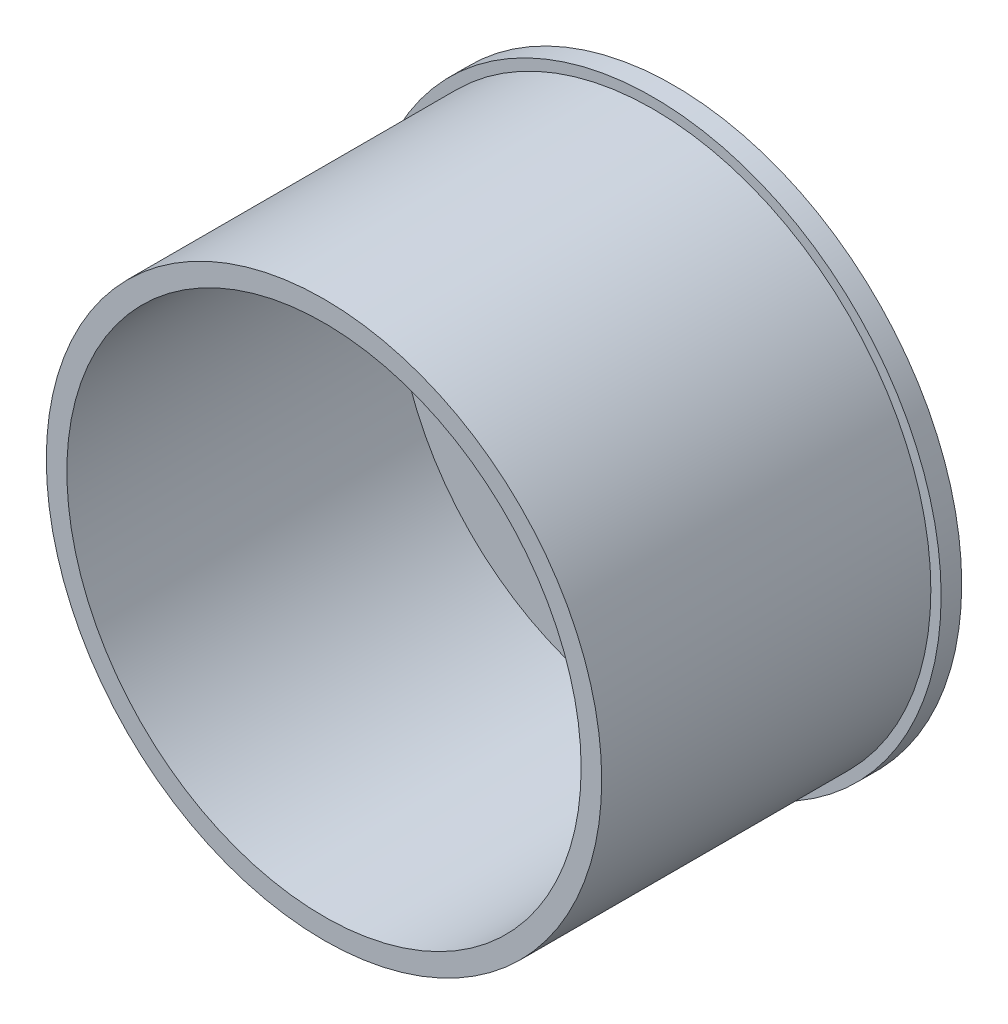
SolidWorks part; units mm, degrees
material "6061 Alloy"
ref_plane "Front Plane" through (0, 0, 0) normal (0, 0, 1) x (1, 0, 0)
ref_plane "Top Plane" through (0, 0, 0) normal (0, 1, 0) x (1, 0, 0)
ref_plane "Right Plane" through (0, 0, 0) normal (1, 0, 0) x (0, 0, -1)
sketch "Sketch1" plane through (0, 0, 0) normal (0, 0, 1) x (1, 0, 0)
  circle A0 centre (0, 0) radius 88.9
  dimension "D1" = 177.8
extrude "Boss-Extrude1" add sketch "Sketch1" along normal blind 6.35
sketch "Sketch2" plane through (0, 0, 0) normal (0, 0, -1) x (-1, 0, 0)
  line L0 (-0.0917, 3.175) -> (0.0917, -3.175) construction
  line L3 (3.082, 3.2667) -> (3.2654, -3.0833)
  line L4 (-3.2654, 3.0833) -> (-3.082, -3.2667)
  arc A2 (3.082, 3.2667) -> (-3.2654, 3.0833) centre (-0.0917, 3.175) ccw
  arc A3 (-3.082, -3.2667) -> (3.2654, -3.0833) centre (0.0917, -3.175) ccw
  circle A4 centre (19.05, 0) radius 3.302
  point P2 (0, 0)
  dimension "D2" = 6.35
  dimension "D3" = 6.604
  dimension "D1" = 6.35
  dimension "D4" = 19.05
extrude "Cut-Extrude1" cut sketch "Sketch2" against normal through all
sketch "Sketch3" plane through (0, 0, 6.35) normal (0, 0, 1) x (1, 0, 0)
  circle A0 centre (0, 0) radius 79.375
  circle A2 centre (0, 0) radius 85.725
  dimension "D1" = 6.35
  dimension "D2" = 158.75
extrude "Boss-Extrude2" add sketch "Sketch3" along normal blind 101.6
